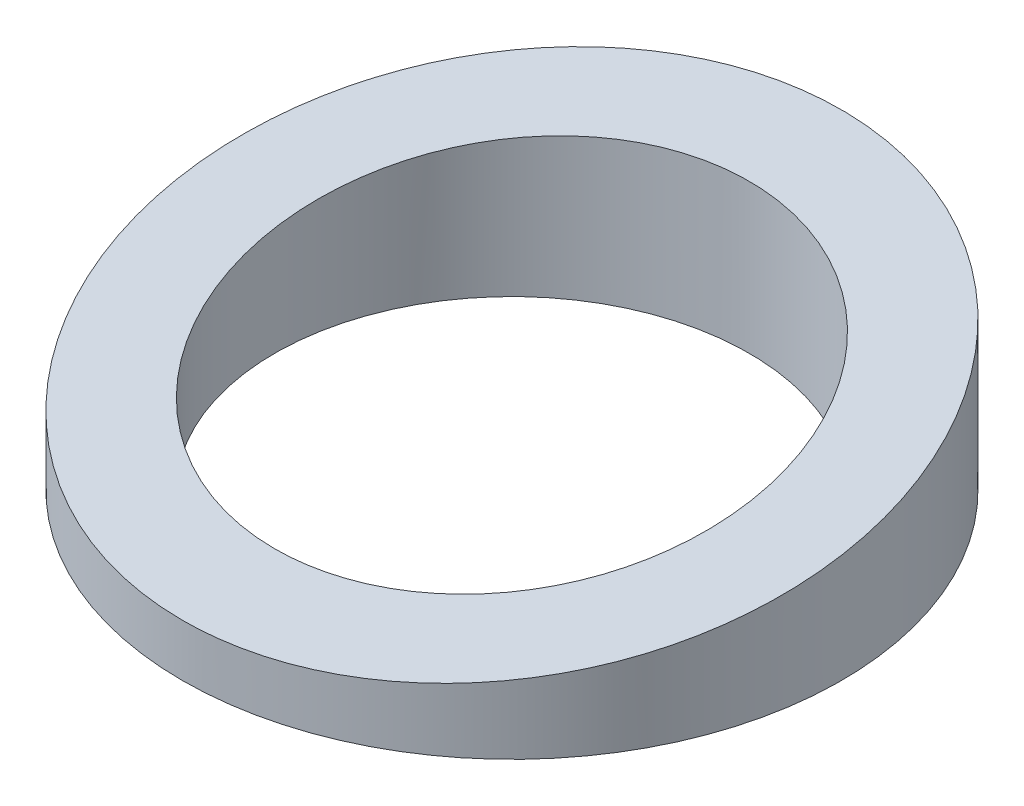
SolidWorks part; units mm, degrees
ref_plane "Front Plane" through (0, 0, 0) normal (0, 0, 1) x (1, 0, 0)
ref_plane "Top Plane" through (0, 0, 0) normal (0, 1, 0) x (1, 0, 0)
ref_plane "Right Plane" through (0, 0, 0) normal (1, 0, 0) x (0, 0, -1)
sketch "Sketch1" plane through (0, 0, 0) normal (0, 1, 0) x (1, 0, 0)
  circle A0 centre (0, 0) radius 3.175
  dimension "D1" = 6.35
extrude "Boss-Extrude1" add sketch "Sketch1" along normal blind 1.5875
sketch "Sketch2" plane through (0, 0, 0) normal (1, 0, 0) x (0, 0, -1)
  line L0 (3.175, 1.5875) -> (-3.175, 0.5032)
  line L1 (3.175, 1.5875) -> (-3.175, 1.5875) construction
  line L2 (-3.175, 0.5032) -> (-3.175, 1.5875)
  line L3 (-3.175, 1.5875) -> (-3.175, 0) construction
  line L4 (-3.175, 1.5875) -> (3.175, 1.5875)
  line L5 (3.175, 0) -> (3.175, 1.5875) construction
  dimension "D1" = 99.69
extrude "Cut-Extrude2" cut sketch "Sketch2" against normal through all both and the other way through all
sketch "Sketch3" plane through (0, 0, 0) normal (0, -1, 0) x (1, 0, 0)
  circle A0 centre (0, 0) radius 2.286
  dimension "D1" = 4.572
extrude "Cut-Extrude3" cut sketch "Sketch3" against normal through all and the other way through all
